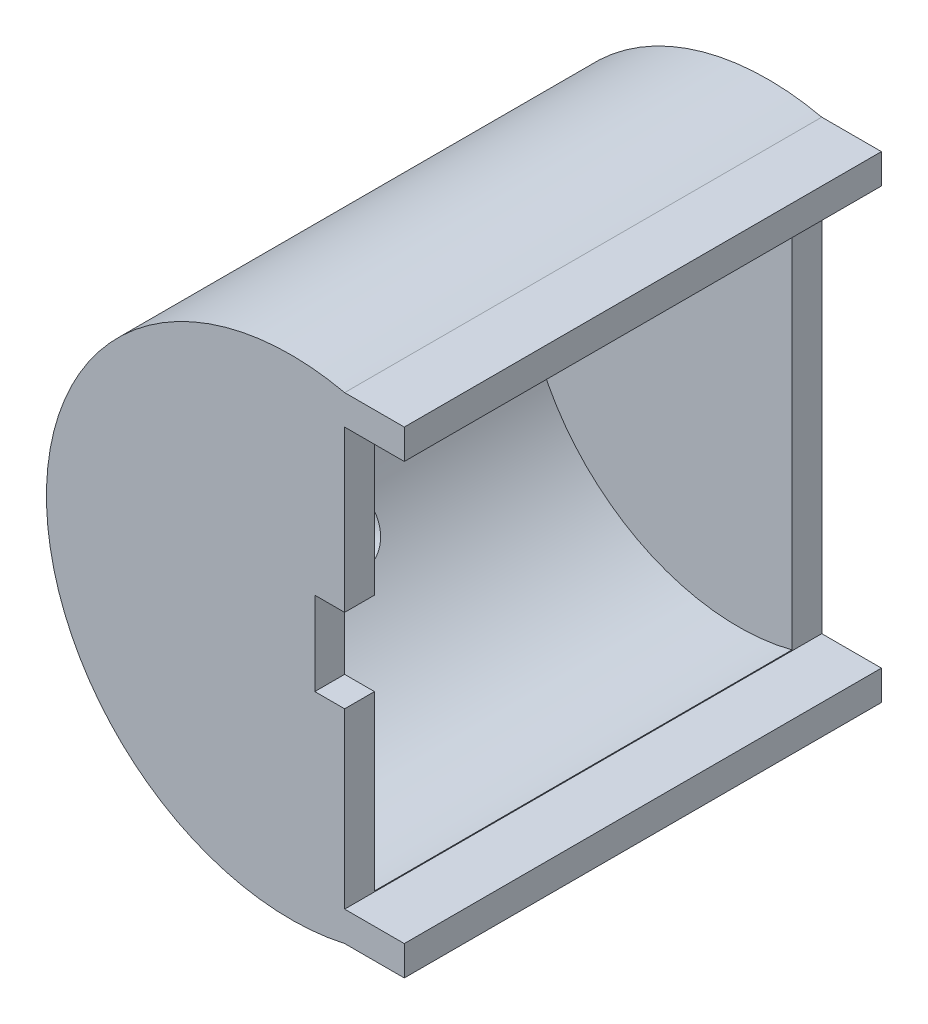
SolidWorks part; units mm, degrees
ref_plane "Front Plane" through (0, 0, 0) normal (0, 0, 1) x (1, 0, 0)
ref_plane "Top Plane" through (0, 0, 0) normal (0, 1, 0) x (1, 0, 0)
ref_plane "Right Plane" through (0, 0, 0) normal (1, 0, 0) x (0, 0, -1)
sketch "Sketch2" plane through (0, 0, 0) normal (0, 0, 1) x (1, 0, 0)
  line L0 (0, -50.8) -> (0, 0)
  line L1 (0, 0) -> (0, 50.8)
  arc A0 (0, 50.8) -> (0, -50.8) centre (-11.43, 0) ccw
  point P3 (-63.5, 0)
  dimension "D1" = 50.8
  dimension "D2" = 50.8
  dimension "D3" = 63.5
extrude "Boss-Extrude1" add sketch "Sketch2" along normal blind 101.6 contours L1 A0 L0
shell "Shell1" thickness 6.35
sketch "Sketch3" plane through (0, 0, 101.6) normal (0, 0, 1) x (1, 0, 0)
  line L0 (0, -50.8) -> (0, 50.8) construction
  line L1 (0, 10.2746) -> (-6.35, 10.2746)
  line L2 (0, 10.2746) -> (0, -7.5054)
  line L3 (0, -7.5054) -> (-6.35, -7.5054)
  line L4 (-6.35, 10.2746) -> (-6.35, -7.5054)
  dimension "D1" = 17.78
  dimension "D2" = 6.35
extrude "Cut-Extrude1" cut sketch "Sketch3" against normal blind 6.35
sketch "Sketch4" plane through (0, 0, 101.6) normal (0, 0, 1) x (1, 0, 0)
  line L1 (0, 50.8) -> (12.7, 50.8)
  line L2 (0, 50.8) -> (0, 44.45)
  line L3 (0, 44.45) -> (12.7, 44.45)
  line L4 (12.7, 50.8) -> (12.7, 44.45)
  line L5 (0, -50.8) -> (12.7, -50.8)
  line L6 (0, -50.8) -> (0, -44.45)
  line L7 (0, -44.45) -> (12.7, -44.45)
  line L8 (12.7, -50.8) -> (12.7, -44.45)
  dimension "D1" = 12.7
  dimension "D2" = 6.35
  dimension "D3" = 6.35
extrude "Boss-Extrude2" add sketch "Sketch4" against normal blind 101.6 contours L2 L1 L4 L3
sketch "Sketch6" plane through (0, 0, 101.6) normal (0, 0, 1) x (1, 0, 0)
  line L0 (0, -50.8) -> (0, -7.5054) construction
  line L1 (0, -50.8) -> (12.7, -50.8)
  line L2 (0, -50.8) -> (0, -44.45)
  line L3 (0, -44.45) -> (12.7, -44.45)
  line L4 (12.7, -50.8) -> (12.7, -44.45)
  dimension "D1" = 6.35
  dimension "D2" = 12.7
extrude "Boss-Extrude3" add sketch "Sketch6" against normal blind 101.6 contours L2 L1 L4 L3
hole_wizard "1/2 (0.5) Diameter Hole1" positions "3DSketch2" profile "Sketch8" hole size "1/2" standard "ANSI Inch"
sketch3d "3DSketch2"
  point P0 (-63.4995, -0.2368, 51.1619)
  point P2 (-55.141, -28.2954, 51.4572)
  point P4 (-56.3435, 26.345, 50.8665)
sketch "Sketch8" plane through (-63.4995, -0.2368, 51.1619) normal (0, 0, 1) x (0.0045, -1, 0)
  line L0 (0, 0) -> (0, 11.4355)
  line L1 (0, 11.4355) -> (6.35, 7.62)
  line L2 (6.35, 7.62) -> (6.35, 0)
  line L5 (6.35, 0) -> (0, 0)
  line L10 (0, 11.4355) -> (-6.35, 7.62) construction
  line L11 (0, -6.35) -> (0, 107.95) construction
  dimension "Hole Dia." = 12.7
  dimension "Hole Depth" = 7.62
  dimension "Drill Angle" = 118
